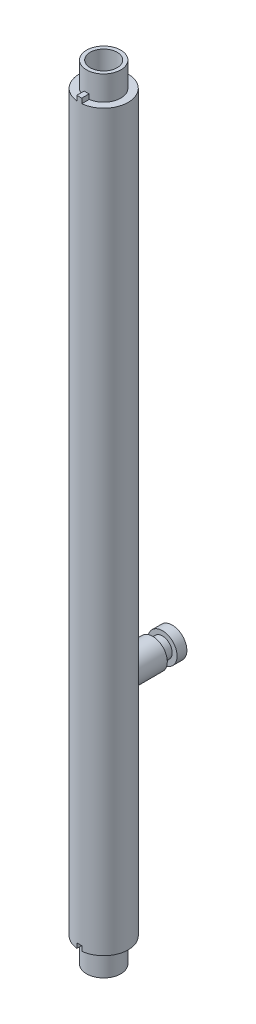
SolidWorks part; units mm, degrees
material "1060 Alloy"
ref_plane "Front Plane" through (0, 0, 0) normal (0, 0, 1) x (1, 0, 0)
ref_plane "Top Plane" through (0, 0, 0) normal (0, 1, 0) x (1, 0, 0)
ref_plane "Right Plane" through (0, 0, 0) normal (1, 0, 0) x (0, 0, -1)
sketch "Sketch1" plane through (0, 0, 0) normal (0, 1, 0) x (1, 0, 0)
  circle A0 centre (0, 0) radius 5
  dimension "D1" = 10
extrude "Boss-Extrude1" add sketch "Sketch1" along normal blind 150
ref_plane "Plane1" through (0, 0, -5) normal (0, 0, 1) x (1, 0, 0)
sketch "Sketch4" plane through (0, 0, -5) normal (0, 0, 1) x (1, 0, 0)
  line L0 (0, 0) -> (0, 45)
  circle A0 centre (0, 45) radius 3
  dimension "D1" = 6
extrude "Boss-Extrude2" add sketch "Sketch4" against normal blind 5 and the other way up to surface separate body other way up to face at (0, 150, 5)
sketch "Sketch5" plane through (0, 0, -10) normal (0, 0, -1) x (-1, 0, 0)
  circle A0 centre (0, 45.0741) radius 2
  dimension "D1" = 4
extrude "Boss-Extrude3" add sketch "Sketch5" along normal blind 2
sketch "Sketch6" plane through (0, 0, -12) normal (0, 0, -1) x (-1, 0, 0)
  circle A0 centre (0, 45) radius 3
  dimension "D1" = 6
extrude "Boss-Extrude4" add sketch "Sketch6" along normal blind 2
sketch "Sketch7" plane through (0, 0, 0) normal (0, -1, 0) x (1, 0, 0)
  circle A0 centre (0, 0) radius 3.5
extrude "Boss-Extrude5" add sketch "Sketch7" along normal blind 5
sketch "Sketch8" plane through (0, 150, 0) normal (0, 1, 0) x (1, 0, 0)
  circle A0 centre (0, 0) radius 3.5
extrude "Boss-Extrude6" add sketch "Sketch8" along normal blind 5
sketch "Sketch9" plane through (0, 155, 0) normal (0, 1, 0) x (1, 0, 0)
  circle A0 centre (0, 0) radius 2.75
extrude "Cut-Extrude1" cut sketch "Sketch9" against normal blind 168
sketch "Sketch11" [suppressed] plane through (0, 0, 0) normal (0, -1, 0) x (-1, 0, 0)
  line L0 (3.5, 0) -> (5, 0)
  circle A0 centre (0, 0) radius 3.5 construction
  circle A1 centre (0, 0) radius 3.5 construction
  circle A2 centre (0, 0) radius 5 construction
ref_plane "Plane2" through (0, 0, 5) normal (0, 0, 1) x (1, 0, 0)
sketch "Sketch14" plane through (0, 0, 5) normal (0, 0, 1) x (1, 0, 0)
  line L0 (0, 0) -> (0.5, 0)
  line L1 (-3.5, 0) -> (3.5, 0) construction
  line L2 (0, 0) -> (-0.5, 0)
  line L3 (-0.5, 0) -> (-0.5, 1)
  line L4 (-0.5, 1) -> (0.5, 1)
  line L5 (0.5, 1) -> (0.5, 0)
extrude "Cut-Extrude4" cut sketch "Sketch14" against normal up to surface (1.5 mm away)
ref_plane "Plane3" through (-0.5, 1, 4.9749) normal (0.995, 0, 0.1) x (0.1, 0, -0.995)
sketch "Sketch16" plane through (0, 150, 0) normal (0, 1, 0) x (1, 0, 0)
  line L0 (0.5, -3.5) -> (0.5, -4.9749)
  line L1 (0.5, -3.5) -> (0.5, -3.4641)
  line L2 (0, -10.45) -> (0, 10.45) construction
  line L3 (-0.5, -3.5) -> (-0.5, -3.4641)
  line L4 (-0.5, -3.5) -> (-0.5, -4.9749)
  arc A0 (-0.5, -3.4641) -> (0.5, -3.4641) centre (0, 0) ccw
  arc A1 (-0.5, -4.9749) -> (0.5, -4.9749) centre (0, 0) ccw
extrude "Boss-Extrude7" add sketch "Sketch16" along normal blind 1
ref_plane "Plane4" through (-2.5, 0, 0) normal (1, 0, 0) x (0, 0, -1)
sketch "Sketch18" plane through (-2.5, 0, 0) normal (1, 0, 0) x (0, 0, -1)
  line L0 (12, 45) -> (12, 45.5)
  line L1 (12, 48) -> (12, 42) construction
  line L2 (12, 47.0741) -> (12, 43.0741) construction
  line L3 (12, 45.5) -> (10, 45.5)
  line L4 (10, 42) -> (10, 48) construction
  line L5 (10, 45.5) -> (10, 45)
  line L6 (10, 45) -> (12, 45)
extrude "Boss-Extrude8" add sketch "Sketch18" along normal up to surface (0.5459 mm away)
